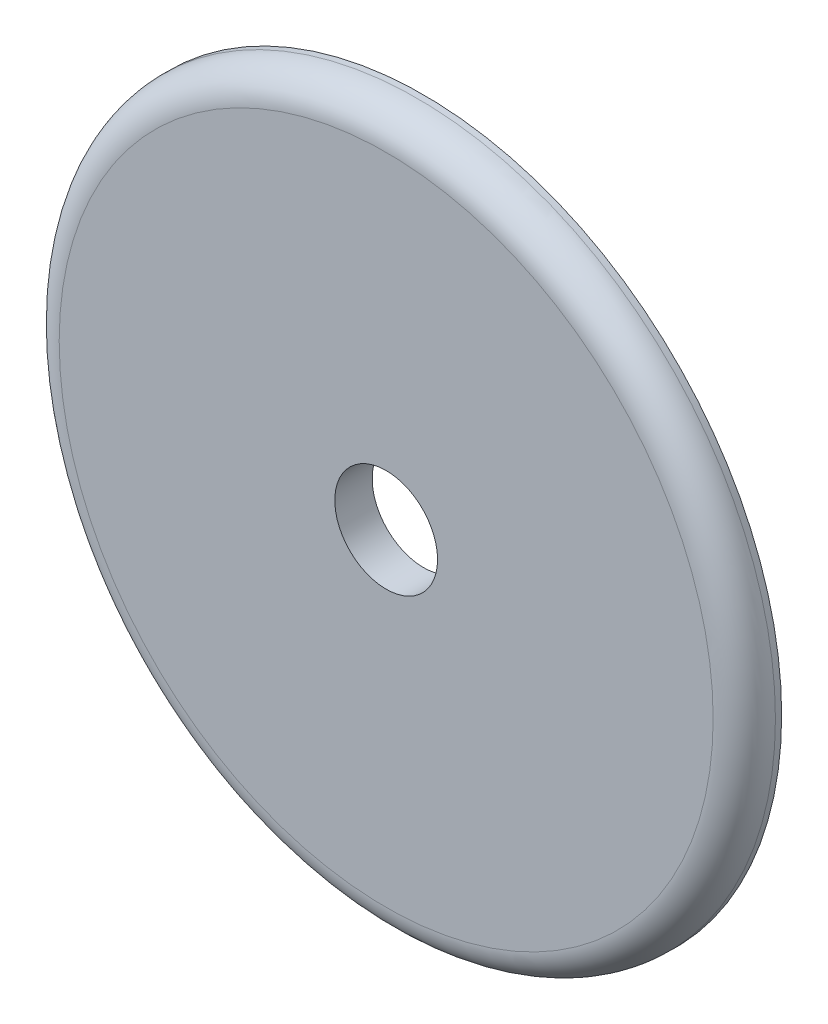
SolidWorks part; units mm, degrees
ref_plane "Front Plane" through (0, 0, 0) normal (0, 0, 1) x (1, 0, 0)
ref_plane "Top Plane" through (0, 0, 0) normal (0, 1, 0) x (1, 0, 0)
ref_plane "Right Plane" through (0, 0, 0) normal (1, 0, 0) x (0, 0, -1)
sketch "Sketch1" plane through (0, 0, 0) normal (0, 0, 1) x (1, 0, 0)
  circle A0 centre (0, 0) radius 11.5
  circle A1 centre (0, 0) radius 1.65
  dimension "D1" = 23
  dimension "D2" = 3.3
extrude "Boss-Extrude1" add sketch "Sketch1" along normal blind 1.2
fillet "Fillet1" radius 1 1 edges at (11.5, 0, 1.2)
